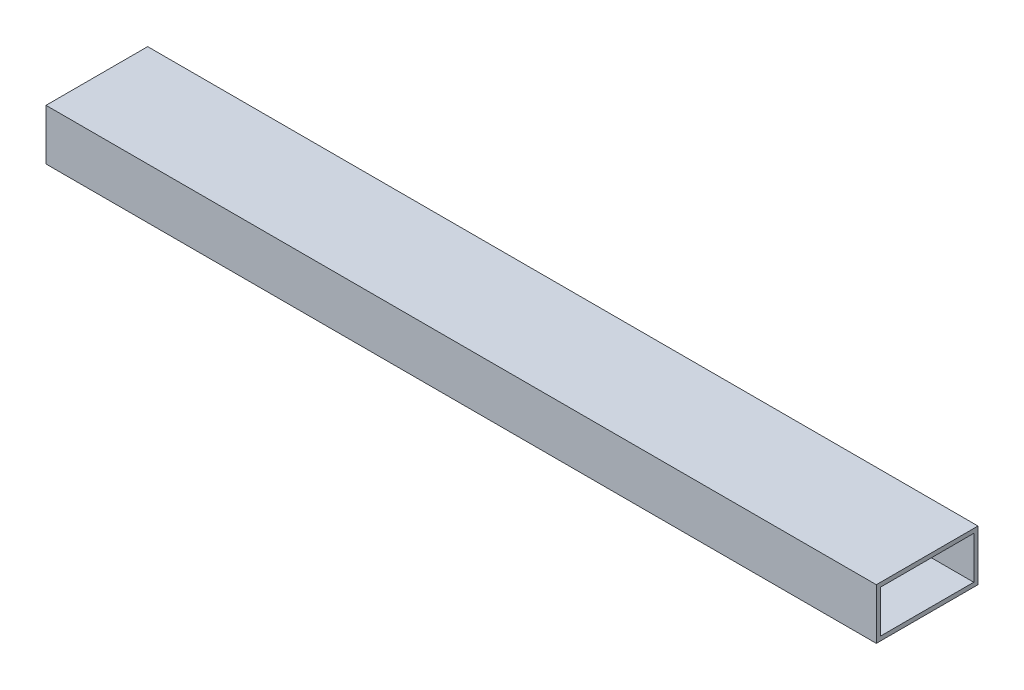
SolidWorks part; units mm, degrees
material "6061 Alloy"
ref_plane "Front Plane" through (0, 0, 0) normal (0, 0, 1) x (1, 0, 0)
ref_plane "Top Plane" through (0, 0, 0) normal (0, 1, 0) x (1, 0, 0)
ref_plane "Right Plane" through (0, 0, 0) normal (1, 0, 0) x (0, 0, -1)
sketch "Sketch1" plane through (0, 0, 0) normal (1, 0, 0) x (0, 0, -1)
  line L13 (73.025, 34.925) -> (3.175, 34.925)
  line L14 (76.2, 0) -> (0, 0)
  line L15 (76.2, 0) -> (76.2, 38.1)
  line L18 (76.2, 38.1) -> (0, 38.1)
  line L19 (0, 0) -> (0, 38.1)
  line L20 (3.175, 3.175) -> (3.175, 34.925)
  line L22 (73.025, 3.175) -> (3.175, 3.175)
  line L23 (73.025, 3.175) -> (73.025, 34.925)
  dimension "D1" = 38.1
  dimension "D3" = 3.175
  dimension "D2" = 76.2
extrude "Boss-Extrude1" add sketch "Sketch1" along normal mid plane 622.3
sketch "Sketch2" plane through (0, 0, -76.2) normal (0, 0, -1) x (-1, 0, 0)
  line L0 (-311.15, 38.1) -> (311.15, 38.1) construction
  line L1 (311.15, 0) -> (311.15, 38.1) construction
  line L2 (-311.15, 0) -> (-311.15, 38.1) construction
  point P0 (260.35, 19.05)
  point P1 (-260.35, 19.05)
  point P2 (0, 0)
  dimension "D1" = 19.05
  dimension "D2" = 50.8
  dimension "D3" = 50.8
hole_wizard "1/4-20 Tapped Hole1" positions "Sketch3" profile "Sketch4" tap size "1/4-20" standard "ANSI Inch"
sketch "Sketch3" plane through (0, 0, -76.2) normal (0, 0, -1) x (-1, 0, 0)
  point P0 (260.35, 19.05)
  point P3 (-260.35, 19.05)
sketch "Sketch4" plane through (-260.35, 19.05, -76.2) normal (1, 0, 0) x (0, 1, 0)
  line L0 (0, 0) -> (0, 3.175)
  line L1 (0, 3.175) -> (2.5527, 3.175)
  line L2 (2.5527, 3.175) -> (2.5527, 0)
  line L5 (2.5527, 0) -> (0, 0)
  line L11 (0, -6.35) -> (0, 107.95) construction
  dimension "Thru Tap Drill Dia." = 5.1054
  dimension "Thru Tap Drill Depth" = 3.175
cosmetic thread "Hole Thread1" parameters "D2"=6.35
cosmetic thread "Hole Thread2" parameters "D2"=6.35
